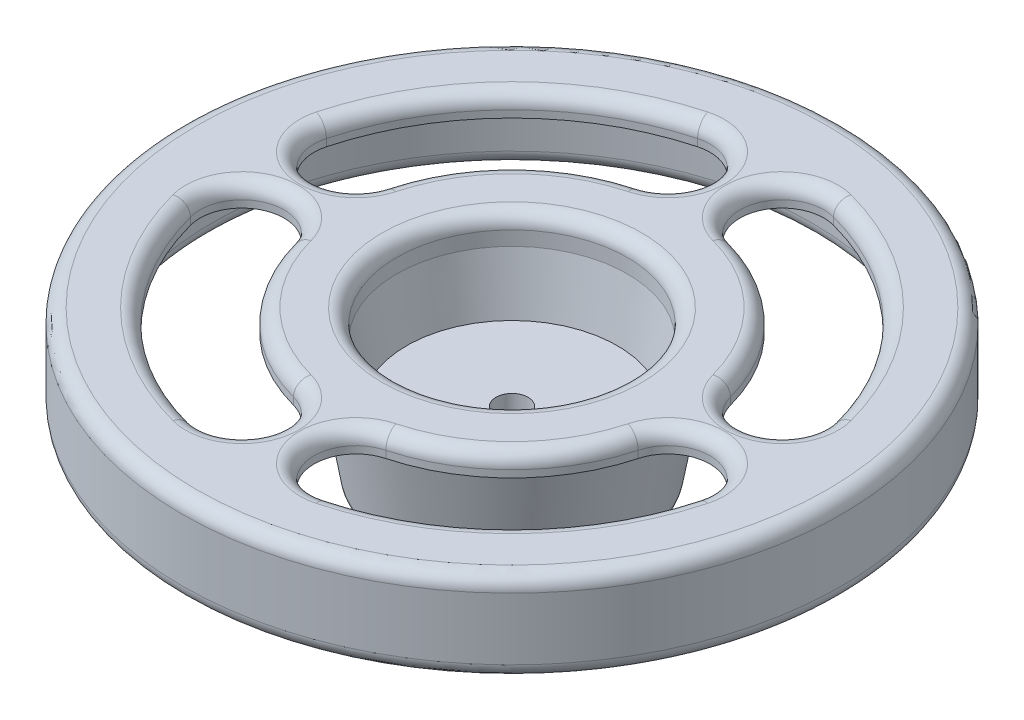
SolidWorks part; units mm, degrees
ref_plane "Front" through (0, 0, 0) normal (0, 0, 1) x (1, 0, 0)
ref_plane "Top" through (0, 0, 0) normal (0, 1, 0) x (1, 0, 0)
ref_plane "Right" through (0, 0, 0) normal (1, 0, 0) x (0, 0, -1)
sketch "Croquis1" plane through (0, 0, 0) normal (1, 0, 0) x (0, 0, -1)
  line L0 (-319.2356, 0) -> (15642.5458, 0) construction
  line L1 (0, -319.2356) -> (0, 15642.5458) construction
  line L3 (-7.3859, 2) -> (-8.0912, 6)
  line L4 (-8.0912, 6) -> (-8.0912, 8)
  line L5 (-8.0912, 8) -> (-23.0912, 8)
  line L6 (-23.0912, 8) -> (-23.0912, -2.75)
  line L7 (-319.2356, 2) -> (15642.5458, 2) construction
  line L8 (-7.3859, 2) -> (0, 2)
  line L9 (0, 2) -> (0, 0)
  line L10 (0, 0) -> (-3.25, 0)
  line L11 (-3.25, 0) -> (-3.25, -2.75)
  line L12 (-3.25, -2.75) -> (-23.0912, -2.75)
  dimension "D1" = 2
  dimension "D2" = 3.25
  dimension "D3" = 2
  dimension "D4" = 100
  dimension "D5" = 15
  dimension "D6" = 4
  dimension "D7" = 2.75
  dimension "D8" = 3.25
revolve "Revolución1" add sketch "Croquis1" angle 360 about L9
sketch "Croquis2" plane through (0, 2, 0) normal (0, 1, 0) x (1, 0, 0)
  circle A0 centre (0, 0) radius 1.125
  dimension "D1" = 2.25
extrude "Cortar-Extruir1" cut sketch "Croquis2" against normal through all
sketch "Croquis3" plane through (0, 0, 0) normal (1, 0, 0) x (0, 0, -1)
  line L0 (-1003.7548, -7.5) -> (48996.2452, -7.5) construction
  line L1 (23.0912, 8) -> (-23.0912, 8) construction
  line L2 (-21, -7.5) -> (-21, 6.5)
  line L3 (-21, 6.5) -> (-10, 6.5)
  line L4 (-10, 6.5) -> (-7.5314, -7.5)
  line L5 (0, -1000) -> (0, 49000) construction
  line L7 (-21, -7.5) -> (-7.5314, -7.5)
  dimension "D1" = 14
  dimension "D2" = 100
  dimension "D3" = 11
  dimension "D4" = 21
  dimension "D5" = 1.5
revolve "Cortar-Revolución1" cut sketch "Croquis3" angle 360 about L5
sketch "Croquis5" plane through (0, 8, 0) normal (0, 1, 0) x (1, 0, 0)
  line L0 (-1000, 0) -> (49000, 0) construction
  line L1 (0, -1000) -> (0, 49000) construction
  line L2 (-707.1068, -707.1068) -> (34648.2323, 34648.2323) construction
  line L3 (-707.1068, 707.1068) -> (34648.2323, -34648.2323) construction
  circle A0 centre (0, 0) radius 15 construction
  circle A1 centre (0, 0) radius 19 construction
  circle A2 centre (0, 0) radius 12.5 construction
  arc A3 (3.9979, 14.9205) -> (14.9205, 3.9979) centre (0, 0) cw construction
  arc A4 (17.767, 4.7606) -> (4.7606, 17.767) centre (0, 0) ccw
  arc A5 (12.0741, 3.2352) -> (3.2352, 12.0741) centre (0, 0) ccw
  arc A6 (12.0741, 3.2352) -> (17.767, 4.7606) centre (14.9205, 3.9979) ccw
  arc A7 (4.7606, 17.767) -> (3.2352, 12.0741) centre (3.9979, 14.9205) ccw
  arc A8 (14.9205, -3.9979) -> (3.9979, -14.9205) centre (0, 0) cw construction
  arc A9 (4.7606, -17.767) -> (17.767, -4.7606) centre (0, 0) ccw
  arc A10 (3.2352, -12.0741) -> (12.0741, -3.2352) centre (0, 0) ccw
  arc A11 (3.2352, -12.0741) -> (4.7606, -17.767) centre (3.9979, -14.9205) ccw
  arc A12 (17.767, -4.7606) -> (12.0741, -3.2352) centre (14.9205, -3.9979) ccw
  arc A13 (-3.9979, -14.9205) -> (-14.9205, -3.9979) centre (0, 0) cw construction
  arc A14 (-17.767, -4.7606) -> (-4.7606, -17.767) centre (0, 0) ccw
  arc A15 (-12.0741, -3.2352) -> (-3.2352, -12.0741) centre (0, 0) ccw
  arc A16 (-12.0741, -3.2352) -> (-17.767, -4.7606) centre (-14.9205, -3.9979) ccw
  arc A17 (-4.7606, -17.767) -> (-3.2352, -12.0741) centre (-3.9979, -14.9205) ccw
  arc A18 (-14.9205, 3.9979) -> (-3.9979, 14.9205) centre (0, 0) cw construction
  arc A19 (-4.7606, 17.767) -> (-17.767, 4.7606) centre (0, 0) ccw
  arc A20 (-3.2352, 12.0741) -> (-12.0741, 3.2352) centre (0, 0) ccw
  arc A21 (-3.2352, 12.0741) -> (-4.7606, 17.767) centre (-3.9979, 14.9205) ccw
  arc A22 (-17.767, 4.7606) -> (-12.0741, 3.2352) centre (-14.9205, 3.9979) ccw
  point P22 (10.9226, 10.9226)
  point P32 (10.9226, -10.9226)
  point P39 (-10.9226, -10.9226)
  point P46 (-10.9226, 10.9226)
  point P51 (0, 0)
  dimension "D1" = 30
  dimension "D2" = 38
  dimension "D3" = 25
  dimension "D6" = 4
extrude "Cortar-Extruir3" cut sketch "Croquis5" against normal blind 12
fillet "Redondeo1" radius 1 20 edges at (0, 8, 8.0912) (-1.1515, 8, -15.6832) (-15.6832, 8, -1.1515) (-8.8388, 8, -8.8388) (-13.0063, 8, -13.0063) (0, 8, 23.0912) (1.1515, 8, -15.6832) (13.0063, 8, -13.0063) (8.8388, 8, -8.8388) (15.6832, 8, -1.1515) (15.6832, 8, 1.1515) (8.8388, 8, 8.8388) (13.0063, 8, 13.0063) (1.1515, 8, 15.6832) (-1.1515, 8, 15.6832) (-13.0063, 8, 13.0063) (-15.6832, 8, 1.1515) (-8.8388, 8, 8.8388) (0, -2.75, 3.25) (0, -2.75, -8.369)
sketch "Croquis6" plane through (0, 0, 0) normal (1, 0, 0) x (0, 0, -1)
  line L0 (-1000, 0) -> (49000, 0) construction
  line L1 (0, -1000) -> (0, 49000) construction
  line L2 (-23.0912, 7) -> (-23.0912, -2.75) construction
  line L3 (-1009.5589, -4.3493) -> (48990.4411, -4.3493) construction
  line L5 (-23.0912, -4.3493) -> (-15.9567, -4.3493)
  line L8 (-15.9567, -4.3493) -> (-15.9567, 1.6507)
  line L9 (-15.9567, 1.6507) -> (-23.0912, 1.6507)
  line L10 (-23.0912, -4.3493) -> (-23.0912, 1.6507)
  dimension "D1" = 6
revolve "Cortar-Revolución2" cut sketch "Croquis6" angle 360 about L1
fillet "Redondeo2" radius 1 2 edges at (0, 1.6507, -21) (0, 1.6507, -23.0912)
